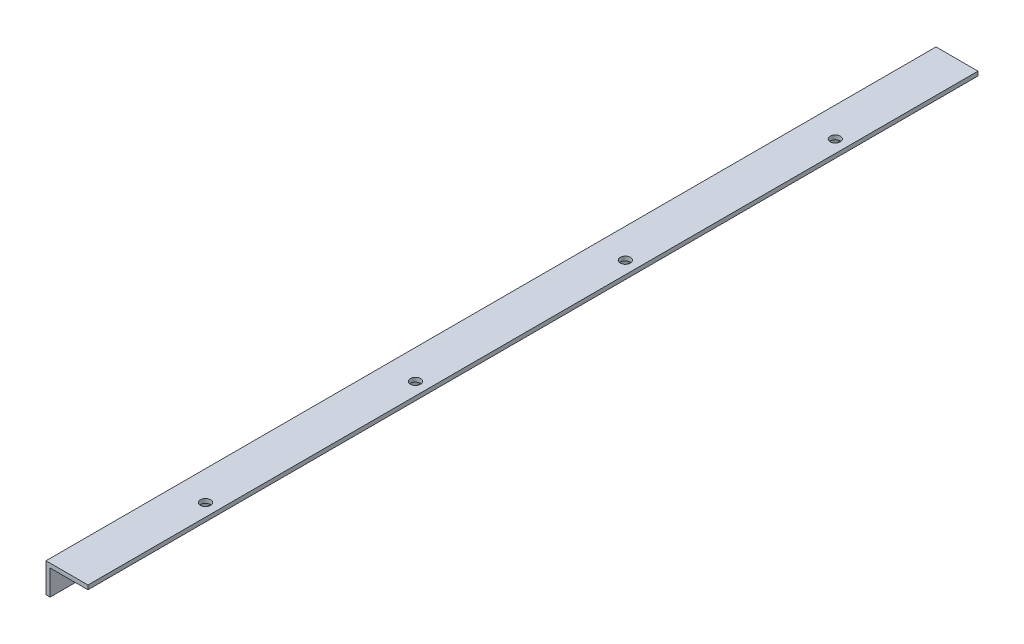
SolidWorks part; units mm, degrees
material "Простая углеродистая сталь"
ref_plane "Спереди" through (0, 0, 0) normal (0, 0, 1) x (1, 0, 0)
ref_plane "Сверху" through (0, 0, 0) normal (0, 1, 0) x (1, 0, 0)
ref_plane "Справа" through (0, 0, 0) normal (1, 0, 0) x (0, 0, -1)
sketch "Эскиз1" plane through (0, 0, 0) normal (0, 0, 1) x (1, 0, 0)
  line L0 (0, 0) -> (0, 7)
  line L1 (0, 7) -> (10, 7)
  line L2 (10, 7) -> (10, 6)
  line L3 (10, 6) -> (1, 6)
  line L4 (1, 6) -> (1, 0)
  line L5 (1, 0) -> (0, 0)
  dimension "D1" = 1
  dimension "D2" = 9
  dimension "D3" = 7
extrude "Бобышка-Вытянуть1" add sketch "Эскиз1" along normal blind 212
hole_wizard "Отверстие с зазором M21" positions "Эскиз3" profile "Эскиз2" hole size "M2" standard "DIN"
sketch "Эскиз3" plane through (0, 7, 0) normal (0, 1, 0) x (-1, 0, 0)
  line L0 (-7, 31) -> (-7, 81)
  line L1 (-7, 81) -> (-7, 131)
  line L2 (-7, 131) -> (-7, 181)
  line L3 (-7, 181) -> (-7, 212)
  line L4 (-10, 212) -> (0, 212) construction
  line L6 (-7, 31) -> (-7, 0)
  line L7 (-10, 0) -> (0, 0) construction
  line L9 (0, 212) -> (0, 0) construction
  point P0 (-7, 131)
  point P1 (-7, 81)
  point P3 (-7, 31)
  point P5 (-7, 181)
  dimension "D1" = 50
  dimension "D2" = 7
sketch "Эскиз2" plane through (7, 7, 131) normal (1, 0, 0) x (0, 0, 1)
  line L0 (0, 0) -> (0, 5.721)
  line L1 (0, 5.721) -> (1.2, 5)
  line L2 (1.2, 5) -> (1.2, 0)
  line L5 (1.2, 0) -> (0, 0)
  line L10 (0, 5.721) -> (-1.2, 5) construction
  line L11 (0, -6.35) -> (0, 107.95) construction
  dimension "Диаметр отверстия" = 2.4
  dimension "Глубина отверстия" = 5
  dimension "Угол заточки сверла" = 118
